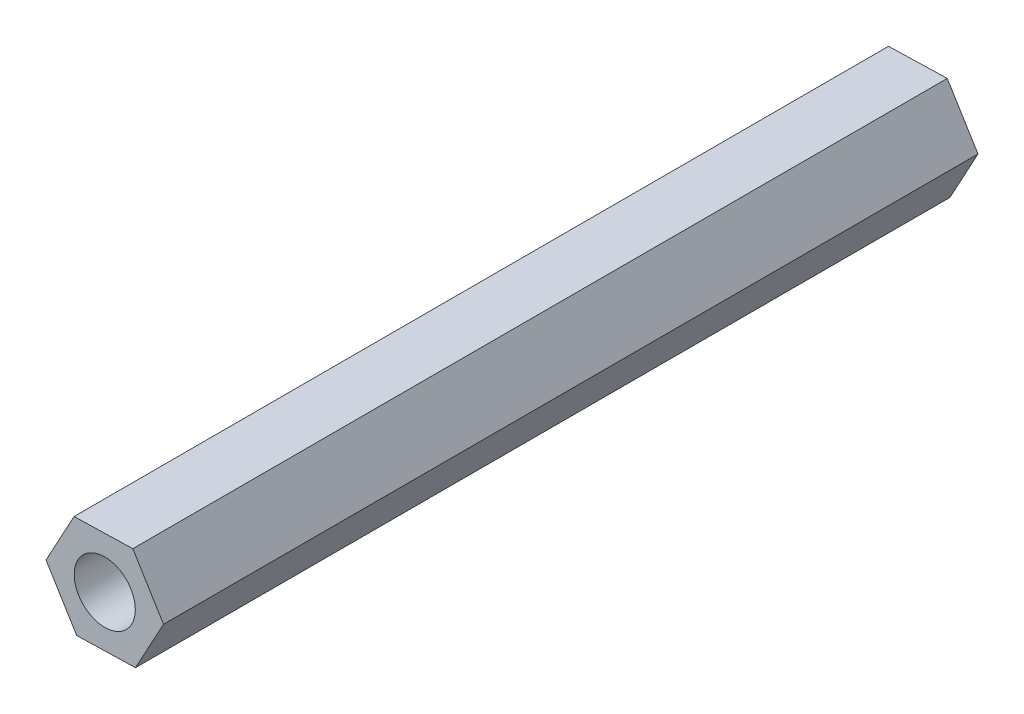
SolidWorks part; units mm, degrees
material "1.4000 (X6Cr13)"
ref_plane "Plan de face" through (0, 0, 0) normal (0, 0, 1) x (1, 0, 0)
ref_plane "Plan de dessus" through (0, 0, 0) normal (0, 1, 0) x (1, 0, 0)
ref_plane "Plan de droite" through (0, 0, 0) normal (1, 0, 0) x (0, 0, -1)
sketch "Esquisse1" plane through (0, 0, 0) normal (0, 0, 1) x (1, 0, 0)
  line L1 (1.3775, 2.5369) -> (-1.5083, 2.4614)
  line L2 (-1.5083, 2.4614) -> (-2.8858, -0.0755)
  line L3 (-2.8858, -0.0755) -> (-1.3775, -2.5369)
  line L4 (-1.3775, -2.5369) -> (1.5083, -2.4614)
  line L5 (1.5083, -2.4614) -> (2.8858, 0.0755)
  line L6 (2.8858, 0.0755) -> (1.3775, 2.5369)
  circle A0 centre (0, 0) radius 2.5 construction
  circle A1 centre (0, 0) radius 1.5
  dimension "D1" = 3
extrude "Boss.-Extru.1" add sketch "Esquisse1" along normal blind 40
